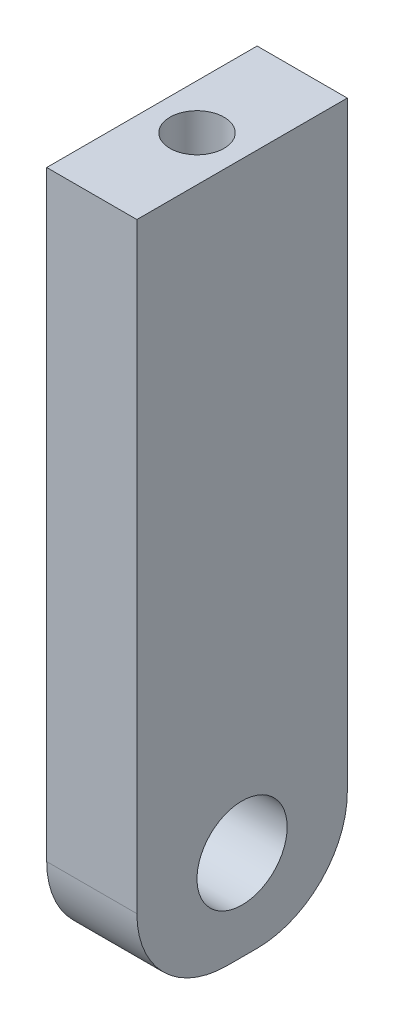
SolidWorks part; units mm, degrees
ref_plane "前视基准面" through (0, 0, 0) normal (0, 0, 1) x (1, 0, 0)
ref_plane "上视基准面" through (0, 0, 0) normal (0, 1, 0) x (1, 0, 0)
ref_plane "右视基准面" through (0, 0, 0) normal (1, 0, 0) x (0, 0, -1)
sketch "草图1" plane through (0, 0, 0) normal (0, 0, 1) x (1, 0, 0)
  line L6 (0, 0.5463) -> (0, -22.4537)
  line L7 (0, -22.4537) -> (3, -22.4537)
  line L8 (3, -22.4537) -> (3, 0.5463)
  line L9 (3, 0.5463) -> (0, 0.5463)
  dimension "D1" = 23
  dimension "D2" = 3
extrude "凸台-拉伸1" add sketch "草图1" along normal blind 7
sketch "草图3" plane through (0, 0.5463, 0) normal (0, 1, 0) x (1, 0, 0)
  line L0 (0, -7) -> (0, 0) construction
  line L1 (3, 0) -> (0, 0) construction
  circle A0 centre (1.5, -3.5) radius 0.9
  point P6 (0, -3.5)
  point P7 (1.5, 0)
  dimension "D1" = 1.8
sketch "草图4" plane through (3, 0, 0) normal (1, 0, 0) x (0, 0, -1)
  line L0 (-7, -22.4537) -> (0, -22.4537) construction
  line L1 (-7, -22.4537) -> (-7, 0.5463) construction
  circle A0 centre (-3.5, -19.4537) radius 1.5
  dimension "D1" = 3
  dimension "D2" = 3
  dimension "D3" = 3.5
extrude "切除-拉伸2" cut sketch "草图4" against normal through all
fillet "圆角1" radius 3 2 edges at (1.5, -22.4537, 7) (1.5, -22.4537, 0)
extrude "切除-拉伸4" cut sketch "草图3" against normal blind 7
